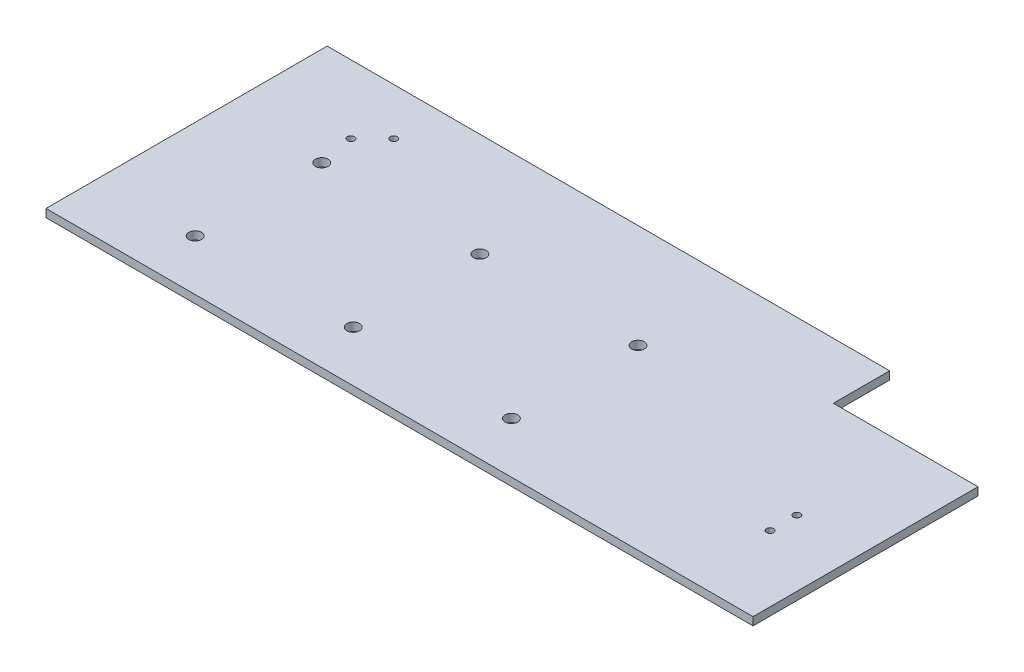
SolidWorks part; units mm, degrees
other "Markup1"
sketch "Sketch4" plane through (-552.45, -6.35, -222.25) normal (-0.3259, -0.6642, -0.6728) x (-0.9221, 0.3804, 0.0712)
sketch "Sketch11" plane through (-552.45, -39.4589, -222.25) normal (-0.3259, -0.6642, -0.6728) x (-0.9221, 0.3804, 0.0712)
sketch "Sketch13" plane through (-552.45, -39.4589, -222.25) normal (-0.3259, -0.6642, -0.6728) x (-0.9221, 0.3804, 0.0712)
sketch "Sketch15" plane through (-552.45, -39.4589, -222.25) normal (-0.3259, -0.6642, -0.6728) x (-0.9221, 0.3804, 0.0712)
sketch "Sketch17" plane through (-552.45, -39.4589, -222.25) normal (-0.3259, -0.6642, -0.6728) x (-0.9221, 0.3804, 0.0712)
sketch "Sketch19" plane through (-558.8, 0, -222.25) normal (-0.3259, -0.6642, -0.6728) x (-0.9221, 0.3804, 0.0712)
sketch "Sketch24" plane through (-558.8, 0, -222.25) normal (-0.3259, -0.6642, -0.6728) x (-0.9221, 0.3804, 0.0712)
sketch "Sketch26" plane through (-558.8, 0, -222.25) normal (-0.3259, -0.6642, -0.6728) x (-0.9221, 0.3804, 0.0712)
sketch "Sketch28" plane through (-558.8, 0, -222.25) normal (-0.3259, -0.6642, -0.6728) x (-0.9221, 0.3804, 0.0712)
sketch "Sketch30" plane through (-558.8, 0, -222.25) normal (-0.3259, -0.6642, -0.6728) x (-0.9221, 0.3804, 0.0712)
other "Markup2"
sketch "Sketch5" plane through (-552.45, -6.35, -222.25) normal (-0.3259, -0.6642, -0.6728) x (-0.9221, 0.3804, 0.0712)
sketch "Sketch12" plane through (-552.45, -39.4589, -222.25) normal (-0.3259, -0.6642, -0.6728) x (-0.9221, 0.3804, 0.0712)
sketch "Sketch14" plane through (-552.45, -39.4589, -222.25) normal (-0.3259, -0.6642, -0.6728) x (-0.9221, 0.3804, 0.0712)
sketch "Sketch16" plane through (-552.45, -39.4589, -222.25) normal (-0.3259, -0.6642, -0.6728) x (-0.9221, 0.3804, 0.0712)
sketch "Sketch18" plane through (-552.45, -39.4589, -222.25) normal (-0.3259, -0.6642, -0.6728) x (-0.9221, 0.3804, 0.0712)
sketch "Sketch20" plane through (-558.8, 0, -222.25) normal (-0.3259, -0.6642, -0.6728) x (-0.9221, 0.3804, 0.0712)
sketch "Sketch25" plane through (-558.8, 0, -222.25) normal (-0.3259, -0.6642, -0.6728) x (-0.9221, 0.3804, 0.0712)
sketch "Sketch27" plane through (-558.8, 0, -222.25) normal (-0.3259, -0.6642, -0.6728) x (-0.9221, 0.3804, 0.0712)
sketch "Sketch29" plane through (-558.8, 0, -222.25) normal (-0.3259, -0.6642, -0.6728) x (-0.9221, 0.3804, 0.0712)
sketch "Sketch31" plane through (-558.8, 0, -222.25) normal (-0.3259, -0.6642, -0.6728) x (-0.9221, 0.3804, 0.0712)
ref_plane "Front Plane" through (0, 0, 0) normal (0, 0, 1) x (1, 0, 0)
ref_plane "Top Plane" through (0, 0, 0) normal (0, 1, 0) x (1, 0, 0)
ref_plane "Right Plane" through (0, 0, 0) normal (1, 0, 0) x (0, 0, -1)
sketch "Sketch1" plane through (0, 0, 0) normal (0, 1, 0) x (1, 0, 0)
  line L0 (0, 0) -> (0, 177.8)
  line L1 (0, 177.8) -> (-114.3, 177.8)
  line L2 (-114.3, 177.8) -> (-114.3, 222.25)
  line L3 (-114.3, 222.25) -> (-558.8, 222.25)
  line L4 (-558.8, 222.25) -> (-558.8, 0)
  line L5 (-558.8, 0) -> (0, 0)
  dimension "D1" = 177.8
  dimension "D2" = 114.3
  dimension "D3" = 558.8
  dimension "D4" = 222.25
extrude "Boss-Extrude1" add sketch "Sketch1" along normal blind 6.35
sketch "Sketch2" plane through (0, 0, 0) normal (0, -1, 0) x (1, 0, 0)
  line L1 (0, 0) -> (0, -177.8) construction
  line L6 (0, -107.95) -> (-33.1089, -107.95) construction
  line L7 (-33.1089, -107.95) -> (-33.1089, -44.45) construction
  line L10 (0, -177.8) -> (-114.3, -177.8) construction
  line L11 (-6.35, -44.45) -> (-33.1089, -44.45) construction
  line L12 (-33.1089, -44.45) -> (-39.4589, -44.45) construction
  line L13 (-39.4589, -44.45) -> (-39.4589, -107.95) construction
  line L14 (-39.4589, -107.95) -> (-33.1089, -107.95) construction
  line L15 (-39.4589, -107.95) -> (-64.8589, -107.95) construction
  line L17 (-64.8589, -107.95) -> (-64.8589, -44.45) construction
  line L18 (-64.8589, -44.45) -> (-39.4589, -44.45) construction
  line L19 (-52.1589, -44.45) -> (-52.1589, -107.95) construction
  line L20 (-64.8589, -86.7833) -> (-39.4589, -86.7833) construction
  line L21 (-64.8589, -65.6167) -> (-39.4589, -65.6167) construction
  line L22 (-33.1089, -44.45) -> (-509.3589, -44.45) construction
  line L23 (-509.3589, -44.45) -> (-509.3589, -151.3205) construction
  line L24 (-509.3589, -151.3205) -> (-509.3589, -100.5205) construction
  line L25 (-509.3589, -100.5205) -> (-503.0089, -100.5205) construction
  line L26 (-503.0089, -100.5205) -> (-503.0089, -202.1205) construction
  line L27 (-503.0089, -202.1205) -> (-509.3589, -202.1205) construction
  line L28 (-509.3589, -202.1205) -> (-509.3589, -151.3205) construction
  line L29 (-503.0089, -151.3205) -> (-452.2089, -151.3205) construction
  line L30 (-503.0089, -202.1205) -> (-452.2089, -202.1205) construction
  line L31 (-452.2089, -202.1205) -> (-452.2089, -151.3205) construction
  line L32 (-452.2089, -202.1205) -> (-503.0089, -151.3205) construction
  line L33 (-452.2089, -202.1205) -> (-469.1422, -185.1872) construction
  line L34 (-469.1422, -185.1872) -> (-486.0756, -168.2538) construction
  line L35 (-486.0756, -168.2538) -> (-503.0089, -151.3205) construction
  circle A0 centre (-52.1589, -86.7833) radius 2.7781
  circle A1 centre (-52.1589, -65.6167) radius 2.7781
  circle A2 centre (-469.1422, -185.1872) radius 2.7781
  circle A3 centre (-486.0756, -168.2538) radius 2.7781
  dimension "D9" = 5.5562
  dimension "D16" = 5.5562
  dimension "D1" = 33.1089
  dimension "D2" = 6.35
  dimension "D3" = 25.4
  dimension "D4" = 69.85
  dimension "D5" = 26.7589
  dimension "D6" = 63.5
  dimension "D7" = 21.1667
  dimension "D8" = 21.1667
  dimension "D10" = 476.25
  dimension "D11" = 106.8705
  dimension "D12" = 50.8
  dimension "D13" = 50.8
  dimension "D14" = 6.35
  dimension "D15" = 50.8
sketch "Sketch10" plane through (0, 6.35, 0) normal (0, 1, 0) x (1, 0, 0)
  line L0 (-481.076, 40.132) -> (-481.076, 0) construction
  line L1 (-481.076, 222.25) -> (-481.076, 180.34) construction
  line L2 (-558.8, 40.132) -> (-546.1, 40.132) construction
  line L3 (-114.3, 222.25) -> (-558.8, 222.25) construction
  line L4 (-481.076, 180.34) -> (-481.076, 140.208) construction
  line L5 (-558.8, 222.25) -> (-558.8, 0) construction
  line L6 (-546.1, 40.132) -> (-481.076, 40.132) construction
  line L7 (-558.8, 0) -> (0, 0) construction
  circle A0 centre (-481.076, 40.132) radius 5
  circle A1 centre (-356.108, 40.132) radius 5
  circle A2 centre (-231.14, 40.132) radius 5
  circle A3 centre (-356.108, 140.208) radius 5
  circle A4 centre (-231.14, 140.208) radius 5
  circle A5 centre (-481.076, 140.208) radius 5
  dimension "D3" = 10
  dimension "D4" = 12.7
  dimension "D6" = 124.968
  dimension "D7" = 100.076
  dimension "D8" = 40.132
  dimension "D9" = 65.024
  dimension "D1" = 3
  dimension "D2" = 2
extrude "Cut-Extrude3" cut sketch "Sketch10" against normal through all both and the other way through all
extrude "Cut-Extrude4" cut sketch "Sketch2" against normal through all
sketch "Sketch23" plane through (0, 6.35, 0) normal (0, 1, 0) x (1, 0, 0)
  line L0 (-356.108, 140.208) -> (-231.14, 140.208) construction
  line L1 (-368.808, 152.908) -> (-368.808, 127.508) construction
  line L2 (-356.108, 140.208) -> (-368.808, 140.208) construction
  line L3 (-368.808, 152.908) -> (-218.44, 152.908)
  line L4 (-218.44, 152.908) -> (-218.44, 127.508)
  line L5 (-218.44, 127.508) -> (-368.808, 127.508)
  line L6 (-231.14, 140.208) -> (-218.44, 140.208) construction
  circle A0 centre (-356.108, 140.208) radius 5 construction
  circle A2 centre (-231.14, 140.208) radius 5 construction
  point P9 (-356.108, 140.208)
  point P10 (-368.808, 140.208)
  dimension "D1" = 10
  dimension "D2" = 25.4
  dimension "D3" = 12.7
sketch3d "3DSketch2"
  line L0 (-558.8, 6.35, 0) -> (-292.1, 6.35, 0) construction
  line L4 (-292.1, 6.35, 0) -> (-292.1, 6.35, -222.25)
  line L5 (-114.3, 6.35, -222.25) -> (-558.8, 6.35, -222.25) construction
  line L6 (-292.1, 6.35, -222.25) -> (-292.1, 0, -222.25)
  line L7 (-114.3, 0, -222.25) -> (-558.8, 0, -222.25) construction
  line L8 (-292.1, 0, -222.25) -> (-292.1, 0, 0)
  line L9 (-558.8, 0, 0) -> (0, 0, 0) construction
  line L10 (-292.1, 0, 0) -> (-292.1, 6.35, 0)
  dimension "D1" = 266.7
